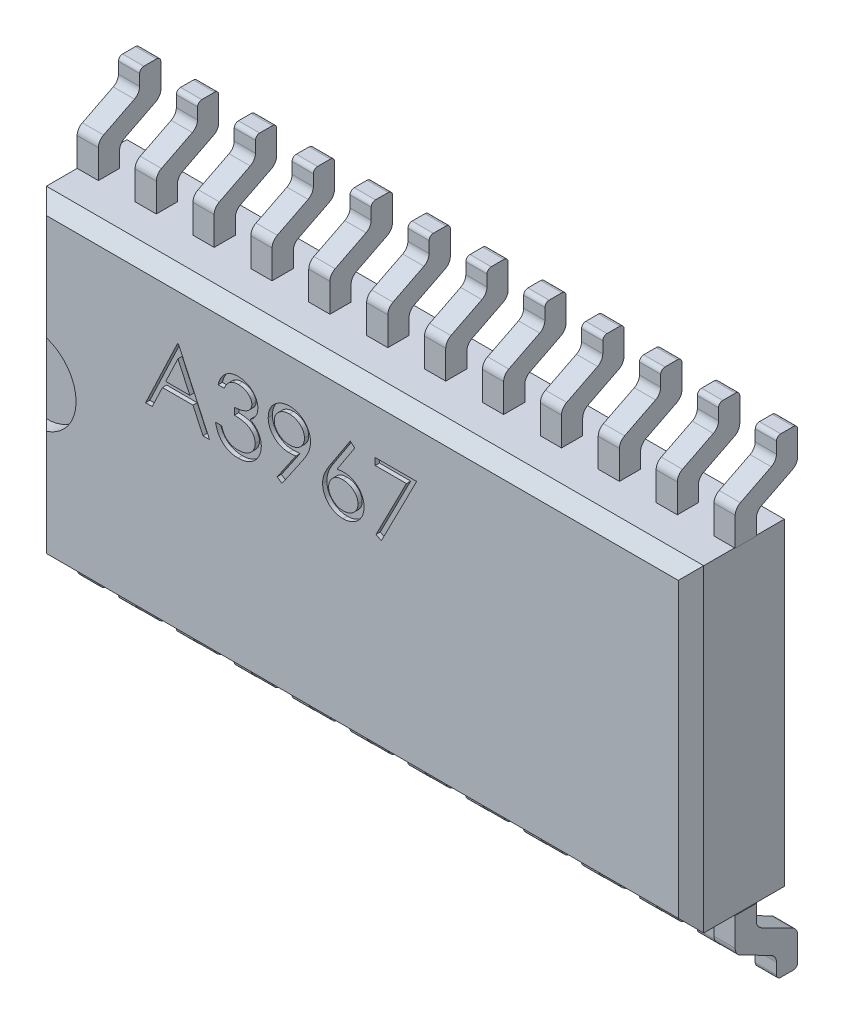
SolidWorks part; units mm, degrees
ref_plane "Front Plane" through (0, 0, 0) normal (0, 0, 1) x (1, 0, 0)
ref_plane "Top Plane" through (0, 0, 0) normal (0, 1, 0) x (1, 0, 0)
ref_plane "Right Plane" through (0, 0, 0) normal (1, 0, 0) x (0, 0, -1)
sketch "Sketch1" plane through (0, 0, 0) normal (0, 0, 1) x (1, 0, 0)
  line L1 (-7.75, 3.75) -> (7.75, 3.75)
  line L2 (-7.75, 3.75) -> (-7.75, -3.75)
  line L3 (-7.75, -3.75) -> (7.75, -3.75)
  line L4 (7.75, 3.75) -> (7.75, -3.75)
  line L5 (-7.75, 3.75) -> (7.75, -3.75) construction
  line L6 (-7.75, -3.75) -> (7.75, 3.75) construction
  point P0 (0, 0)
  dimension "D1" = 15.5
  dimension "D2" = 7.5
extrude "Boss-Extrude1" add sketch "Sketch1" along normal blind 2.5
chamfer "Chamfer1" distance 0.3 angle 45 8 edges at (0, 3.75, 2.5) (0, 3.75, 0) (0, -3.75, 0) (0, -3.75, 2.5) (7.75, 0, 0) (-7.75, 0, 0) (7.75, 0, 2.5) (-7.75, 0, 2.5)
sketch "Sketch2" plane through (-7.75, 0, 0) normal (-1, 0, 0) x (0, 0, 1)
  line L0 (0.973, 3.75) -> (0.973, 4.1132)
  line L1 (2.2, 3.75) -> (0.3, 3.75) construction
  line L2 (0.851, 4.3118) -> (0.122, 4.6809)
  line L3 (0, 4.8795) -> (0, 5.45)
  line L4 (0.1, 5.55) -> (0.4, 5.55)
  line L5 (0.5, 5.45) -> (0.5, 5.1868)
  line L6 (0.622, 4.9882) -> (1.351, 4.6191)
  line L7 (1.473, 4.4205) -> (1.473, 3.75)
  line L8 (1.473, 3.75) -> (0.973, 3.75)
  line L9 (0, 0) -> (4.1052, 0) construction
  line L10 (0.1, -5.55) -> (0.4, -5.55)
  line L11 (0.5, -5.45) -> (0.5, -5.1868)
  line L12 (0.622, -4.9882) -> (1.351, -4.6191)
  line L13 (1.473, -4.4205) -> (1.473, -3.75)
  line L14 (1.473, -3.75) -> (0.973, -3.75)
  line L15 (0.973, -3.75) -> (0.973, -4.1132)
  line L16 (0.851, -4.3118) -> (0.122, -4.6809)
  line L17 (0, -4.8795) -> (0, -5.45)
  arc A0 (0, 4.8795) -> (0.122, 4.6809) centre (0.2226, 4.8795) ccw
  arc A1 (0.973, 4.1132) -> (0.851, 4.3118) centre (0.7504, 4.1132) ccw
  arc A2 (1.473, 4.4205) -> (1.351, 4.6191) centre (1.2504, 4.4205) ccw
  arc A3 (0.622, 4.9882) -> (0.5, 5.1868) centre (0.7226, 5.1868) cw
  arc A4 (0.5, 5.45) -> (0.4, 5.55) centre (0.4, 5.45) ccw
  arc A5 (0.1, 5.55) -> (0, 5.45) centre (0.1, 5.45) ccw
  arc A6 (0.1, -5.55) -> (0, -5.45) centre (0.1, -5.45) cw
  arc A7 (0.5, -5.45) -> (0.4, -5.55) centre (0.4, -5.45) cw
  arc A8 (0.622, -4.9882) -> (0.5, -5.1868) centre (0.7226, -5.1868) ccw
  arc A9 (1.473, -4.4205) -> (1.351, -4.6191) centre (1.2504, -4.4205) cw
  arc A10 (0.973, -4.1132) -> (0.851, -4.3118) centre (0.7504, -4.1132) cw
  arc A11 (0, -4.8795) -> (0.122, -4.6809) centre (0.2226, -4.8795) cw
  point P15 (0.973, 4.25)
  point P18 (1.473, 4.5572)
  point P21 (0.5, 5.05)
  point P24 (0.5, 5.55)
  dimension "D8" = 0.2226
  dimension "D9" = 0.1
  dimension "D1" = 0.5
  dimension "D2" = 1.8
  dimension "D3" = 0.5
  dimension "D4" = 0.5
  dimension "D5" = 0.5
  dimension "D6" = 0.5
  dimension "D7" = 0.8072
extrude "Boss-Extrude2" add sketch "Sketch2" against normal blind 0.5
pattern_linear "LPattern1" count 12 spacing 1.365 along (1, 0, 0) of "Boss-Extrude2"
sketch "Sketch3" plane through (0, 0, 2.5) normal (0, 0, 1) x (1, 0, 0)
  line L0 (-7.75, -3.75) -> (-7.75, 3.75) construction
  circle A0 centre (-7.75, 0) radius 1
  dimension "D1" = 2
extrude "Cut-Extrude1" cut sketch "Sketch3" against normal blind 0.3
sketch "Sketch4" plane through (0, 0, 2.5) normal (0, 0, 1) x (1, 0, 0)
  text T0 "A3967" font "Century Gothic" height in points 6
extrude "Cut-Extrude2" cut sketch "Sketch4" against normal blind 0.1
sketch "Sketch5" plane through (-7.75, 0, 0) normal (-1, 0, 0) x (0, 0, 1)
  line L0 (1.473, 3.75) -> (1.473, 4.4205) construction
  line L1 (0.973, 3.75) -> (1.473, 3.75)
  line L2 (0.973, 3.75) -> (0.973, 3.76)
  line L3 (0.973, 3.76) -> (1.473, 3.76)
  line L4 (1.473, 3.75) -> (1.473, 3.76)
  line L5 (1.473, -4.4205) -> (1.473, -3.75) construction
  line L6 (0.973, -3.75) -> (1.473, -3.75)
  line L7 (0.973, -3.75) -> (0.973, -3.76)
  line L8 (0.973, -3.76) -> (1.473, -3.76)
  line L9 (1.473, -3.75) -> (1.473, -3.76)
  dimension "D1" = 0.01
  dimension "D2" = 0.01
extrude "Cut-Extrude3" cut sketch "Sketch5" against normal blind 0.01
